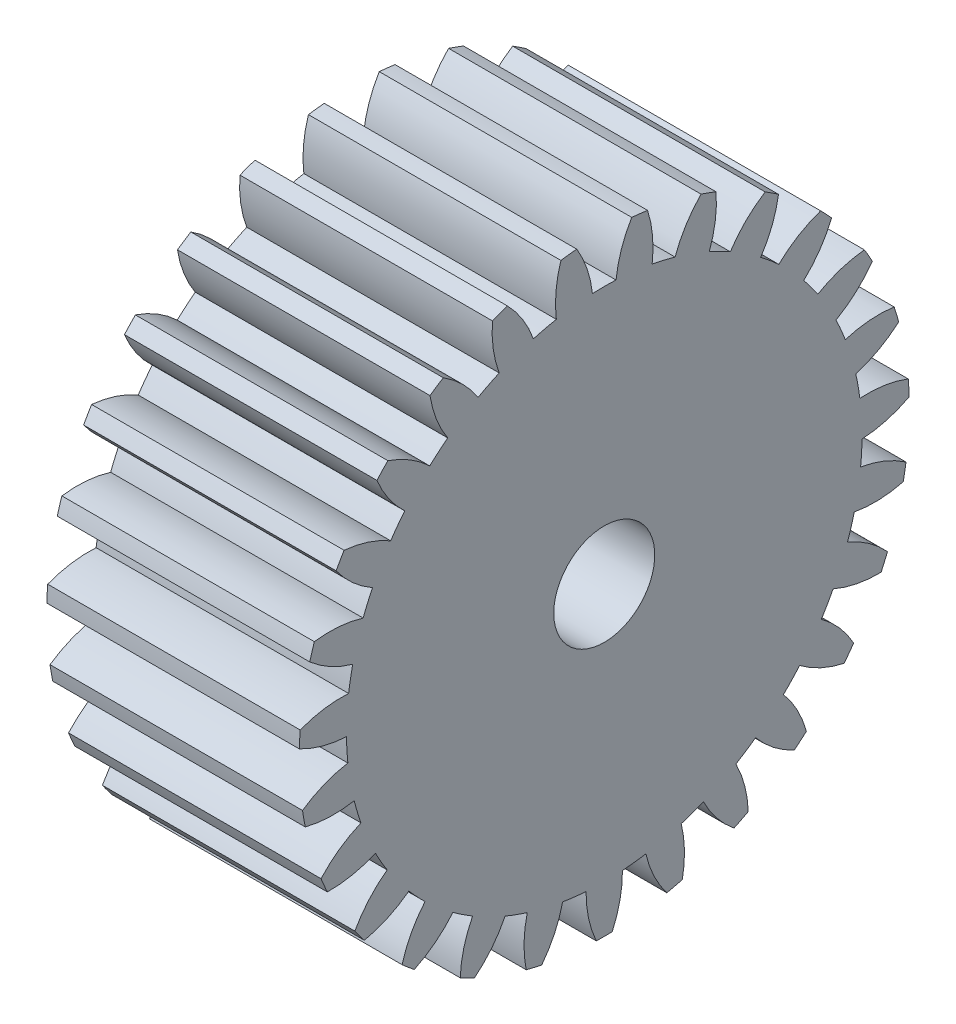
SolidWorks part; units mm, degrees
ref_plane "Plane1" through (0, 0, 0) normal (0, 0, 1) x (1, 0, 0)
ref_plane "Plane2" through (0, 0, 0) normal (0, 1, 0) x (1, 0, 0)
ref_plane "Plane3" through (0, 0, 0) normal (1, 0, 0) x (0, 0, -1)
other "Configuration Table"
sketch "HoldingSke" plane through (0, 0, 0) normal (0, 1, 0) x (1, 0, 0)
  line L0 (0, 0) -> (0.3564, -0.1816)
  line L1 (-15, 0) -> (100, 0) construction
  line L2 (0, 0) -> (-2.1039, 2.3779)
  line L3 (0, 0) -> (-11.863, 4.5341)
  line L4 (0, 0) -> (7.6947, 3.9207)
  line L5 (0, 0) -> (-46.8476, -17.4728)
  line L6 (0, 0) -> (-24.8689, -16.7791)
  line L7 (-2.1039, 2.3779) -> (8.6586, 51.2059)
  line L8 (-76.2, 54.61) -> (-73.9, 54.61)
  line L9 (-67.7845, 28.3722) -> (-49.3413, 33.142)
  line L10 (-76.2, 71.12) -> (104.1128, 71.12)
  line L11 (0, 0) -> (-30, 0)
  line L12 (-76.2, 101.6) -> (-76.113, 101.6)
  line L13 (24.9733, 27.94) -> (52.9518, 28.4284)
  line L14 (24.9733, 27.94) -> (24.9743, 27.94)
  line L15 (24.9733, 27.94) -> (100.4006, 29.5858)
  line L16 (-63.627, -2.5) -> (-12.827, -2.5)
  circle A0 centre (0, 0) radius 6
  circle A1 centre (0, 0) radius 30.624
  circle A2 centre (0, 0) radius 37.5
  circle A3 centre (0, 0) radius 6
  dimension "MHD" = 61.248
  dimension "Hub_dia" = 75
  dimension "Bore" = 12
  dimension "MBD" = 12
  dimension "Num_teeth" = 27
  dimension "Pitch" = 0.4
  dimension "Overall_len" = 50
  dimension "Show_teeth" = 27
  dimension "Thickness" = 30
  dimension "OAL" = 50.0001
  dimension "T_dim" = 2.3
  dimension "Ap" = 14.5
  dimension "H" = 19.05
  dimension "Pitch_radius" = 180.3128
  dimension "Width" = 30
  dimension "Backlash" = 0.087
  dimension "Addendum_fac" = 1
  dimension "Dedendum_fac" = 1.25
  dimension "Clearance_fac" = 0.25
  dimension "Dedendum_add" = 0.001
  dimension "Module" = 2.5
sketch "BasProSke" plane through (0, 0, 0) normal (0, 1, 0) x (1, 0, 0)
  line L0 (-10, 0) -> (60, 0) construction
  line L1 (0, 0) -> (0, 36.25)
  line L2 (0, 0) -> (30, 0)
  line L3 (30, 0) -> (30, 36.25)
  line L4 (30, 36.25) -> (0, 36.25)
  dimension "Thickness" = 30
  dimension "Diameter" = 72.5
revolve "Base-Revolve" add sketch "BasProSke" angle 360 about L0
sketch "TooCutSke" plane through (0, 0, 0) normal (1, 0, 0) x (0, 0, -1)
  line L1 (0, 0) -> (0, 107) construction
  line L2 (0, 0) -> (-2.1146, 33.6837) construction
  line L3 (0, 0) -> (-7.825, 66.9471) construction
  line L4 (-2.1146, 33.6837) -> (-3.9125, 33.4735) construction
  arc A0 (1.4005, 30.592) -> (-1.4005, 30.592) centre (0, 0) ccw
  arc A1 (3.2803, 36.1268) -> (-3.2803, 36.1268) centre (0, 0) ccw
  circle A2 centre (0, 0) radius 33.75 construction
  circle A3 centre (0, 0) radius 32.675 construction
  arc A4 (-1.4005, 30.592) -> (-3.2803, 36.1268) centre (-14.8201, 29.1208) ccw
  arc A5 (3.2803, 36.1268) -> (1.4005, 30.592) centre (14.8201, 29.1208) ccw
  dimension "Root_dia" = 61.248
  dimension "Overcut_dia" = 72.5508
  dimension "Pitch_dia" = 67.5
  dimension "Base_dia" = 65.35
  dimension "Flank_rad" = 13.5
  dimension "Half_ang" = 6.667
  dimension "Half_CT" = 1.8101
extrude "ToothCut" cut sketch "TooCutSke" along normal through all
fillet "Breaks" [suppressed] radius 0.05
fillet "RootFillets" [suppressed] radius 0.626
pattern_circular "TeethCuts" count 27 every 13.333 about axis through (-10, 0, 0) along (1, 0, 0) of "ToothCut", "RootFillets", "Breaks"
sketch "HubNeaOneSke" plane through (0, 0, 0) normal (-1, 0, 0) x (0, 0, 1)
  circle A0 centre (0, 0) radius 30.624
  dimension "Diameter" = 61.248
extrude "HubNearOne" [suppressed] add sketch "HubNeaOneSke" along normal blind 20.0001
sketch "HubNeaBotSke" plane through (0, 0, 0) normal (-1, 0, 0) x (0, 0, 1)
  circle A0 centre (0, 0) radius 30.624
  dimension "Diameter" = 61.248
extrude "HubNearBoth" [suppressed] add sketch "HubNeaBotSke" along normal blind 10
ref_plane "FarPln" through (30, 0, 0) normal (1, 0, 0) x (0, 0, -1)
sketch "HubFarSke" plane through (30, 0, 0) normal (1, 0, 0) x (0, 0, -1)
  circle A0 centre (0, 0) radius 30.624
  dimension "Diameter" = 61.248
extrude "HubFar" [suppressed] add sketch "HubFarSke" along normal blind 10
sketch "BorSke" plane through (0, 0, 0) normal (1, 0, 0) x (0, 0, -1)
  circle A0 centre (0, 0) radius 6
  dimension "Diameter" = 12
extrude "Bore" cut sketch "BorSke" along normal mid plane 100.0001
sketch "KeySke" plane through (0, 0, 0) normal (1, 0, 0) x (0, 0, -1)
  line L0 (-2.5, 0) -> (-2.5, 8.3)
  line L1 (-2.5, 8.3) -> (2.5, 8.3)
  line L2 (2.5, 8.3) -> (2.5, 0)
  line L3 (0, 0) -> (0, 34) construction
  line L4 (-2.5, 0) -> (2.5, 0)
  dimension "Offset" = 8.3
  dimension "Width" = 5
extrude "Keyway" [suppressed] cut sketch "KeySke" along normal mid plane 100.0001
pattern_circular "Keyway2" [suppressed] count 2 every 90 about axis through (-10, 0, 0) along (1, 0, 0)
sketch "Esquisse1" plane through (30, 0, 0) normal (1, 0, 0) x (0, 0, -1)
  circle A0 centre (0, 0) radius 10.5
  circle A1 centre (0, 0) radius 25
  circle A2 centre (0, 25) radius 4
  dimension "D1" = 50
equation "' \"Module@HoldingSke\" = 6.35"
equation "' \"Num_teeth@HoldingSke\" = 12"
equation "' \"Ap@HoldingSke\" =  20"
equation "' \"Ap@HoldingSke\" = 20"
equation "' \"Width@HoldingSke\" = 0.5 * 25.4"
equation "' \"Hub_dia@HoldingSke\"= 1 * 25.4"
equation "' \"Hub_dia@HoldingSke\" = 1 * 25.4"
equation "' \"Overall_len@HoldingSke\" = 1.0 * 25.4"
equation "' \"Bore@HoldingSke\" = 0.75 * 25.4"
equation "' \"T_dim@HoldingSke\" = 0.1 * 25.4"
equation "' \"Width@KeySke\" = 0.25 * 25.4"
equation "' \"Show_teeth@HoldingSke\" = 13"
equation "' \"Backlash@HoldingSke\" = 0.009 * 25.4"
equation "' \"Addendum_fac@HoldingSke\" = 1.0"
equation "' \"Dedendum_fac@HoldingSke\" = 1.25"
equation "' \"Dedendum_add@HoldingSke\" = 0.00005 * 25.4"
equation "' \"Clearance_fac@HoldingSke\" = 0.25"
equation "\"Pitch@HoldingSke\" = 1 / \"Module@HoldingSke\""
equation "\"Overcut_dia@TooCutSke\" = (\"Num_teeth@HoldingSke\" + 2 * \"Addendum_fac@HoldingSke\") / \"Pitch@HoldingSke\" + 0.002 * 25.4"
equation "\"Pitch_dia@TooCutSke\" = \"Num_teeth@HoldingSke\" / \"Pitch@HoldingSke\""
equation "\"Base_dia@TooCutSke\" = \"Num_teeth@HoldingSke\" / \"Pitch@HoldingSke\" * cos((\"Ap@HoldingSke\"  * 3.14159265 / 180))"
equation "\"Root_dia@TooCutSke\" = (\"Num_teeth@HoldingSke\" + 2) / \"Pitch@HoldingSke\" - 2 * (\"Addendum_fac@HoldingSke\" + \"Dedendum_fac@HoldingSke\") / \"Pitch@HoldingSke\" - \"Dedendum_add@HoldingSke\" * 2"
equation "\"Half_ang@TooCutSke\" = 180 / \"Num_teeth@HoldingSke\""
equation "\"Half_CT@TooCutSke\" = \"Num_teeth@HoldingSke\" / \"Pitch@HoldingSke\" * sin((3.14159265 / 2 / \"Num_teeth@HoldingSke\")) / 2 - 7 * \"Backlash@HoldingSke\" / 4"
equation "\"Flank_rad@TooCutSke\" = \"Num_teeth@HoldingSke\" / \"Pitch@HoldingSke\" / 5"
equation "\"Radius@RootFillets\" = \"Clearance_fac@HoldingSke\" / \"Pitch@HoldingSke\" + \"Dedendum_add@HoldingSke\""
equation "\"Break_rad@Breaks\" = 0.02 / \"Pitch@HoldingSke\""
equation "\"Thickness@HoldingSke\" = \"Width@HoldingSke\""
equation "\"OAL@HoldingSke\" = \"Thickness@HoldingSke\""
equation "\"MHD@HoldingSke\" = (\"Num_teeth@HoldingSke\" + 2) / \"Pitch@HoldingSke\" - 2 * (\"Addendum_fac@HoldingSke\" + \"Dedendum_fac@HoldingSke\")  / \"Pitch@HoldingSke\" - \"Dedendum_add@HoldingSke\" * 2"
equation "\"MBD@HoldingSke\" = (\"Num_teeth@HoldingSke\" + 2) / \"Pitch@HoldingSke\" - 2 * (\"Addendum_fac@HoldingSke\" + \"Dedendum_fac@HoldingSke\")  / \"Pitch@HoldingSke\" - \"Dedendum_add@HoldingSke\" * 2 - 0.002 * 25.4"
equation "\"MHD@HoldingSke\" = ((sgn( \"MHD@HoldingSke\" - \"Hub_dia@HoldingSke\" )-1)*( \"MHD@HoldingSke\" - \"Hub_dia@HoldingSke\" ))/-2+ \"Hub_dia@HoldingSke\""
equation "\"MBD@HoldingSke\" = ((sgn( \"MBD@HoldingSke\" - \"Bore@HoldingSke\" )-1)*( \"MBD@HoldingSke\" - \"Bore@HoldingSke\" ))/-2+ \"Bore@HoldingSke\""
equation "\"OAL@HoldingSke\" = ((sgn( \"OAL@HoldingSke\" - \"Overall_len@HoldingSke\" )+1)*( \"OAL@HoldingSke\" - \"Overall_len@HoldingSke\" ))/2 + \"Overall_len@HoldingSke\" + 0.000002 * 25.4"
equation "\"Num_teeth@TeethCuts\" = int( \"Show_teeth@HoldingSke\" ) + 1"
equation "\"Num_teeth@TeethCuts\" = ((sgn( \"Num_teeth@TeethCuts\" - \"Num_teeth@HoldingSke\" )-1)*( \"Num_teeth@TeethCuts\" - \"Num_teeth@HoldingSke\" ))/-2+ \"Num_teeth@HoldingSke\""
equation "\"Num_teeth@TeethCuts\" = ((sgn( \"Num_teeth@TeethCuts\" - 2.0)+1)*( \"Num_teeth@TeethCuts\" - 2.0))/2 +2.0"
equation "\"Angle@TeethCuts\" = 360.0 / \"Num_teeth@HoldingSke\""
equation "\"Diameter@BasProSke\" = (\"Num_teeth@HoldingSke\" + 2 * \"Addendum_fac@HoldingSke\") / \"Pitch@HoldingSke\""
equation "\"Thickness@BasProSke\"  = \"Thickness@HoldingSke\""
equation "' \"Fillet_rad@BasProSke\" =  \"Thickness@HoldingSke\" * 0.05"
equation "' \"Fillet_rad@BasProSke\" = \"Thickness@HoldingSke\" * 0.05"
equation "\"MHD@HoldingSke\" = ((sgn( \"MHD@HoldingSke\" - \"Root_dia@TooCutSke\" )-1)*( \"MHD@HoldingSke\" - \"Root_dia@TooCutSke\" ))/-2+ \"Root_dia@TooCutSke\""
equation "\"Diameter@HubNeaOneSke\" = \"MHD@HoldingSke\""
equation "\"Length@HubNearOne\" = \"OAL@HoldingSke\" - \"Thickness@BasProSke\""
equation "\"Diameter@HubNeaBotSke\" = \"MHD@HoldingSke\""
equation "\"Length@HubNearBoth\" = ( \"OAL@HoldingSke\" - \"Thickness@BasProSke\" ) / 2.0"
equation "\"Thickness@FarPln\" = \"Thickness@BasProSke\""
equation "\"Diameter@HubFarSke\" = \"MHD@HoldingSke\""
equation "\"Length@HubFar\" = ( \"OAL@HoldingSke\" - \"Thickness@BasProSke\" ) / 2.0"
equation "\"Diameter@BorSke\" = \"MBD@HoldingSke\""
equation "\"D1@Bore\" = \"OAL@HoldingSke\" * 2.0"
equation "\"D1@Keyway\" = \"OAL@HoldingSke\" * 2.0"
equation "\"Offset@KeySke\" = \"T_dim@HoldingSke\" + \"MBD@HoldingSke\" / 2.0"
